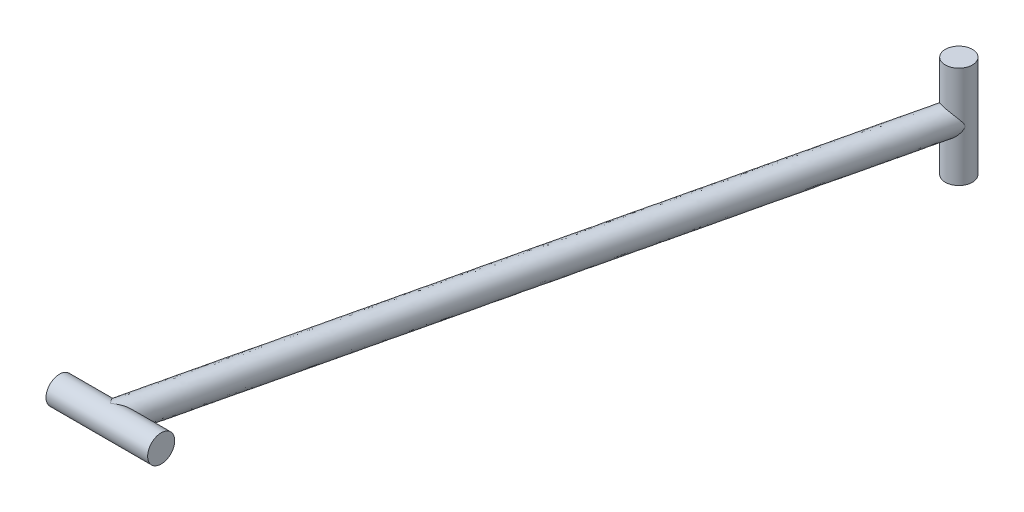
SolidWorks part; units mm, degrees
ref_plane "Front Plane" through (0, 0, 0) normal (0, 0, 1) x (1, 0, 0)
ref_plane "Top Plane" through (0, 0, 0) normal (0, 1, 0) x (1, 0, 0)
ref_plane "Right Plane" through (0, 0, 0) normal (1, 0, 0) x (0, 0, -1)
sketch "Sketch2" plane through (0, 0, 0) normal (0, 0, 1) x (1, 0, 0)
  circle A0 centre (0, 0) radius 2
  dimension "D1" = 4
sketch "Sketch3" plane through (0, 0, 0) normal (0, 1, 0) x (1, 0, 0)
  line L0 (0, 0) -> (23.8512, 101.3719)
  line L1 (-13.6474, 0) -> (13.6474, 0) construction
  point P6 (0, 0)
  dimension "D1" = 76.76
  dimension "D2" = 104.14
sweep "Sweep1" add profiles "Sketch2" path "Sketch3"
sketch "Sketch4" plane through (0, 0, 0) normal (0, 0, 1) x (1, 0, 0)
  line L0 (-7.5, 0) -> (7.5, 0)
  point P4 (0, 0)
  dimension "D1" = 15
sketch "Sketch5" plane through (0, 0, -101.3719) normal (0, 0, -1) x (-1, 0, 0)
  line L0 (-23.8512, -7.5) -> (-23.8512, 7.5)
  circle A0 centre (-23.8512, 0) radius 2.5 construction
  point P3 (-23.8512, 0)
  point P5 (0, 0)
  point P6 (0, 0)
  dimension "D2" = 0
  dimension "D1" = 15
ref_plane "Plane1" through (23.8512, 7.5, -101.3719) normal (0, 1, 0) x (1, 0, 0)
sketch "Sketch6" plane through (23.8512, 7.5, -101.3719) normal (0, 1, 0) x (1, 0, 0)
  circle A0 centre (0, 0) radius 2
  dimension "D1" = 4
sweep "Sweep2" add profiles "Sketch6" path "Sketch5"
ref_plane "Plane2" through (7.5, 0, 0) normal (1, 0, 0) x (0, 0, -1)
sketch "Sketch7" plane through (7.5, 0, 0) normal (1, 0, 0) x (0, 0, -1)
  circle A0 centre (0, 0) radius 2
sweep "Sweep3" add profiles "Sketch7" path "Sketch4"
